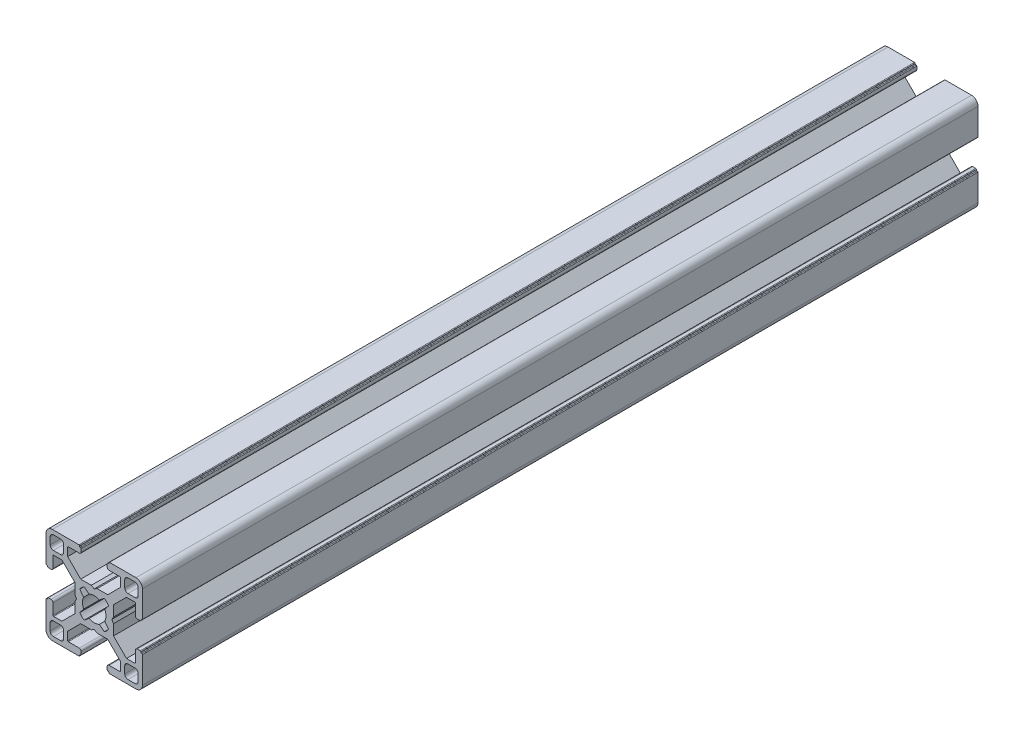
SolidWorks part; units mm, degrees
ref_plane "Front" through (0, 0, 0) normal (0, 0, 1) x (1, 0, 0)
ref_plane "Top" through (0, 0, 0) normal (0, 1, 0) x (1, 0, 0)
ref_plane "Right" through (0, 0, 0) normal (1, 0, 0) x (0, 0, -1)
sketch "Sketch1" plane through (0, 0, 0) normal (0, 0, 1) x (1, 0, 0)
  line L0 (13.7, 12.7) -> (13.7, 10.5)
  line L1 (10.5, 9.5) -> (12.7, 9.5)
  line L2 (9.5, 12.7) -> (9.5, 10.5)
  line L3 (10.5, 13.7) -> (12.7, 13.7)
  line L4 (3.1359, 4.5184) -> (1.6001, 3.2806)
  line L5 (3.2806, 1.6001) -> (4.5053, 3.1547)
  line L6 (6.0045, 0.9) -> (5.4849, 0)
  line L7 (6.0045, 4.2045) -> (6.0045, 0.9)
  line L8 (0, -5.4849) -> (0.9, -6)
  line L9 (0.9, -6) -> (4.2045, -6)
  line L10 (4.2045, -6) -> (8.25, -10.05)
  line L11 (8.25, -10.05) -> (8.25, -12.6)
  line L12 (4.65, -12.8) -> (8.05, -12.8)
  line L13 (4.05, -14.3) -> (4.05, -13.4)
  line L14 (4.25, -14.5) -> (4.35, -14.5)
  line L15 (4.55, -14.8) -> (4.55, -14.7)
  line L16 (4.75, -15) -> (13, -15)
  line L17 (15, -13) -> (15, -4.75)
  line L18 (14.7, -4.55) -> (14.8, -4.55)
  line L19 (14.5, -4.35) -> (14.5, -4.25)
  line L20 (13.4, -4.05) -> (14.3, -4.05)
  line L21 (12.8, -8.05) -> (12.8, -4.65)
  line L22 (12.6, -8.25) -> (10.05, -8.25)
  line L23 (10.05, -8.25) -> (6.0045, -4.2045)
  line L24 (6.0045, -4.2045) -> (6.0045, -0.9)
  line L25 (6.0045, -0.9) -> (5.4849, 0)
  line L26 (10.05, 8.25) -> (6.0045, 4.2045)
  line L27 (12.6, 8.25) -> (10.05, 8.25)
  line L28 (12.8, 8.05) -> (12.8, 4.65)
  line L29 (13.4, 4.05) -> (14.3, 4.05)
  line L30 (14.5, 4.35) -> (14.5, 4.25)
  line L31 (14.7, 4.55) -> (14.8, 4.55)
  line L32 (15, 13) -> (15, 4.75)
  line L33 (4.75, 15) -> (13, 15)
  line L34 (4.55, 14.8) -> (4.55, 14.7)
  line L35 (4.25, 14.5) -> (4.35, 14.5)
  line L36 (4.05, 14.3) -> (4.05, 13.4)
  line L37 (4.65, 12.8) -> (8.05, 12.8)
  line L38 (8.25, 10.05) -> (8.25, 12.6)
  line L39 (4.2045, 6) -> (8.25, 10.05)
  line L40 (0.9, 6) -> (4.2045, 6)
  line L41 (0, 5.4849) -> (0.9, 6)
  line L42 (-13.7, -12.7) -> (-13.7, -10.5)
  line L43 (-10.5, -9.5) -> (-12.7, -9.5)
  line L44 (-9.5, -12.7) -> (-9.5, -10.5)
  line L45 (-10.5, -13.7) -> (-12.7, -13.7)
  line L46 (-3.1359, -4.5184) -> (-1.6001, -3.2806)
  line L47 (-3.2806, -1.6001) -> (-4.5053, -3.1547)
  line L48 (0, 5.4849) -> (-0.9, 6)
  line L49 (-0.9, 6) -> (-4.2045, 6)
  line L50 (-4.2045, 6) -> (-8.25, 10.05)
  line L51 (-8.25, 10.05) -> (-8.25, 12.6)
  line L52 (-4.65, 12.8) -> (-8.05, 12.8)
  line L53 (-4.05, 14.3) -> (-4.05, 13.4)
  line L54 (-4.25, 14.5) -> (-4.35, 14.5)
  line L55 (-4.55, 14.8) -> (-4.55, 14.7)
  line L56 (-4.75, 15) -> (-13, 15)
  line L57 (-15, 13) -> (-15, 4.75)
  line L58 (-14.7, 4.55) -> (-14.8, 4.55)
  line L59 (-14.5, 4.35) -> (-14.5, 4.25)
  line L60 (-13.4, 4.05) -> (-14.3, 4.05)
  line L61 (-12.8, 8.05) -> (-12.8, 4.65)
  line L62 (-12.6, 8.25) -> (-10.05, 8.25)
  line L63 (-10.05, 8.25) -> (-6.0045, 4.2045)
  line L64 (-6.0045, -0.9) -> (-5.4849, 0)
  line L65 (-6.0045, -4.2045) -> (-6.0045, -0.9)
  line L66 (-10.05, -8.25) -> (-6.0045, -4.2045)
  line L67 (-12.6, -8.25) -> (-10.05, -8.25)
  line L68 (-12.8, -8.05) -> (-12.8, -4.65)
  line L69 (-13.4, -4.05) -> (-14.3, -4.05)
  line L70 (-14.5, -4.35) -> (-14.5, -4.25)
  line L71 (-14.7, -4.55) -> (-14.8, -4.55)
  line L72 (-15, -13) -> (-15, -4.75)
  line L73 (-4.75, -15) -> (-13, -15)
  line L74 (-4.55, -14.8) -> (-4.55, -14.7)
  line L75 (-4.25, -14.5) -> (-4.35, -14.5)
  line L76 (-4.05, -14.3) -> (-4.05, -13.4)
  line L77 (3.2806, -1.6001) -> (4.5053, -3.1547)
  line L78 (3.1359, -4.5184) -> (1.6001, -3.2806)
  line L79 (-4.65, -12.8) -> (-8.05, -12.8)
  line L80 (-8.25, -10.05) -> (-8.25, -12.6)
  line L81 (-4.2045, -6) -> (-8.25, -10.05)
  line L82 (-0.9, -6) -> (-4.2045, -6)
  line L83 (0, -5.4849) -> (-0.9, -6)
  line L84 (10.5, -13.7) -> (12.7, -13.7)
  line L85 (9.5, -12.7) -> (9.5, -10.5)
  line L86 (10.5, -9.5) -> (12.7, -9.5)
  line L87 (13.7, -12.7) -> (13.7, -10.5)
  line L88 (-6.0045, 4.2045) -> (-6.0045, 0.9)
  line L89 (-6.0045, 0.9) -> (-5.4849, 0)
  line L90 (-3.2806, 1.6001) -> (-4.5053, 3.1547)
  line L91 (-3.1359, 4.5184) -> (-1.6001, 3.2806)
  line L92 (-10.5, 13.7) -> (-12.7, 13.7)
  line L93 (-9.5, 12.7) -> (-9.5, 10.5)
  line L94 (-10.5, 9.5) -> (-12.7, 9.5)
  line L95 (-13.7, 12.7) -> (-13.7, 10.5)
  line L96 (-23.4857, 0) -> (20.9308, 0) construction
  line L97 (0, 17.9563) -> (0, -17.361) construction
  arc A0 (13.7, 12.7) -> (12.7, 13.7) centre (12.7, 12.7) ccw
  arc A1 (12.7, 9.5) -> (13.7, 10.5) centre (12.7, 10.5) ccw
  arc A2 (9.5, 10.5) -> (10.5, 9.5) centre (10.5, 10.5) ccw
  arc A3 (10.5, 13.7) -> (9.5, 12.7) centre (10.5, 12.7) ccw
  arc A4 (1.6001, 3.2806) -> (-1.6001, 3.2806) centre (0, 0) ccw
  arc A5 (8.25, -12.6) -> (8.05, -12.8) centre (8.05, -12.6) cw
  arc A6 (4.65, -12.8) -> (4.05, -13.4) centre (4.65, -13.4) ccw
  arc A7 (4.05, -14.3) -> (4.25, -14.5) centre (4.25, -14.3) ccw
  arc A8 (4.35, -14.5) -> (4.55, -14.7) centre (4.35, -14.7) cw
  arc A9 (4.55, -14.8) -> (4.75, -15) centre (4.75, -14.8) ccw
  arc A10 (13, -15) -> (15, -13) centre (13, -13) ccw
  arc A11 (15, -4.75) -> (14.8, -4.55) centre (14.8, -4.75) ccw
  arc A12 (14.7, -4.55) -> (14.5, -4.35) centre (14.7, -4.35) cw
  arc A13 (14.5, -4.25) -> (14.3, -4.05) centre (14.3, -4.25) ccw
  arc A14 (13.4, -4.05) -> (12.8, -4.65) centre (13.4, -4.65) ccw
  arc A15 (12.8, -8.05) -> (12.6, -8.25) centre (12.6, -8.05) cw
  arc A16 (4.5053, 3.1547) -> (3.1359, 4.5184) centre (0, 0) ccw
  arc A17 (12.8, 8.05) -> (12.6, 8.25) centre (12.6, 8.05) ccw
  arc A18 (13.4, 4.05) -> (12.8, 4.65) centre (13.4, 4.65) cw
  arc A19 (14.5, 4.25) -> (14.3, 4.05) centre (14.3, 4.25) cw
  arc A20 (14.7, 4.55) -> (14.5, 4.35) centre (14.7, 4.35) ccw
  arc A21 (15, 4.75) -> (14.8, 4.55) centre (14.8, 4.75) cw
  arc A22 (13, 15) -> (15, 13) centre (13, 13) cw
  arc A23 (4.55, 14.8) -> (4.75, 15) centre (4.75, 14.8) cw
  arc A24 (4.35, 14.5) -> (4.55, 14.7) centre (4.35, 14.7) ccw
  arc A25 (4.05, 14.3) -> (4.25, 14.5) centre (4.25, 14.3) cw
  arc A26 (4.65, 12.8) -> (4.05, 13.4) centre (4.65, 13.4) cw
  arc A27 (8.25, 12.6) -> (8.05, 12.8) centre (8.05, 12.6) ccw
  arc A28 (-13.7, -12.7) -> (-12.7, -13.7) centre (-12.7, -12.7) ccw
  arc A29 (-12.7, -9.5) -> (-13.7, -10.5) centre (-12.7, -10.5) ccw
  arc A30 (-9.5, -10.5) -> (-10.5, -9.5) centre (-10.5, -10.5) ccw
  arc A31 (-10.5, -13.7) -> (-9.5, -12.7) centre (-10.5, -12.7) ccw
  arc A32 (-4.5053, -3.1547) -> (-3.1359, -4.5184) centre (0, 0) ccw
  arc A33 (-3.2806, 1.6001) -> (-3.2806, -1.6001) centre (0, 0) ccw
  arc A34 (-8.25, 12.6) -> (-8.05, 12.8) centre (-8.05, 12.6) cw
  arc A35 (-4.65, 12.8) -> (-4.05, 13.4) centre (-4.65, 13.4) ccw
  arc A36 (-4.05, 14.3) -> (-4.25, 14.5) centre (-4.25, 14.3) ccw
  arc A37 (-4.35, 14.5) -> (-4.55, 14.7) centre (-4.35, 14.7) cw
  arc A38 (-4.55, 14.8) -> (-4.75, 15) centre (-4.75, 14.8) ccw
  arc A39 (-13, 15) -> (-15, 13) centre (-13, 13) ccw
  arc A40 (-15, 4.75) -> (-14.8, 4.55) centre (-14.8, 4.75) ccw
  arc A41 (-14.7, 4.55) -> (-14.5, 4.35) centre (-14.7, 4.35) cw
  arc A42 (-14.5, 4.25) -> (-14.3, 4.05) centre (-14.3, 4.25) ccw
  arc A43 (-13.4, 4.05) -> (-12.8, 4.65) centre (-13.4, 4.65) ccw
  arc A44 (-12.8, 8.05) -> (-12.6, 8.25) centre (-12.6, 8.05) cw
  arc A45 (-4.5053, 3.1547) -> (-3.1359, 4.5184) centre (0, 0) cw
  arc A46 (-12.8, -8.05) -> (-12.6, -8.25) centre (-12.6, -8.05) ccw
  arc A47 (-13.4, -4.05) -> (-12.8, -4.65) centre (-13.4, -4.65) cw
  arc A48 (-14.5, -4.25) -> (-14.3, -4.05) centre (-14.3, -4.25) cw
  arc A49 (3.2806, 1.6001) -> (3.2806, -1.6001) centre (0, 0) cw
  arc A50 (4.5053, -3.1547) -> (3.1359, -4.5184) centre (0, 0) cw
  arc A51 (1.6001, -3.2806) -> (-1.6001, -3.2806) centre (0, 0) cw
  arc A52 (-14.7, -4.55) -> (-14.5, -4.35) centre (-14.7, -4.35) ccw
  arc A53 (-15, -4.75) -> (-14.8, -4.55) centre (-14.8, -4.75) cw
  arc A54 (-13, -15) -> (-15, -13) centre (-13, -13) cw
  arc A55 (-4.55, -14.8) -> (-4.75, -15) centre (-4.75, -14.8) cw
  arc A56 (10.5, -13.7) -> (9.5, -12.7) centre (10.5, -12.7) cw
  arc A57 (9.5, -10.5) -> (10.5, -9.5) centre (10.5, -10.5) cw
  arc A58 (12.7, -9.5) -> (13.7, -10.5) centre (12.7, -10.5) cw
  arc A59 (13.7, -12.7) -> (12.7, -13.7) centre (12.7, -12.7) cw
  arc A60 (-4.35, -14.5) -> (-4.55, -14.7) centre (-4.35, -14.7) ccw
  arc A61 (-4.05, -14.3) -> (-4.25, -14.5) centre (-4.25, -14.3) cw
  arc A62 (-4.65, -12.8) -> (-4.05, -13.4) centre (-4.65, -13.4) cw
  arc A63 (-8.25, -12.6) -> (-8.05, -12.8) centre (-8.05, -12.6) ccw
  arc A64 (-10.5, 13.7) -> (-9.5, 12.7) centre (-10.5, 12.7) cw
  arc A65 (-9.5, 10.5) -> (-10.5, 9.5) centre (-10.5, 10.5) cw
  arc A66 (-12.7, 9.5) -> (-13.7, 10.5) centre (-12.7, 10.5) cw
  arc A67 (-13.7, 12.7) -> (-12.7, 13.7) centre (-12.7, 12.7) cw
  point P81 (15, 15)
  point P82 (0, 15)
  point P203 (0, -15)
  point P204 (15, -15)
  point P206 (0, 0)
  point P207 (15, 0)
  point P219 (-15, 0)
  point P220 (-15, -15)
  point P221 (-15, 15)
  dimension "D6" = 7.3
  dimension "D7" = 11
  dimension "D1" = 30
  dimension "D2" = 15
  dimension "D3" = 30
  dimension "D4" = 8.1
  dimension "D5" = 9
  dimension "D8" = 8.1
extrude "Base-Extrude" add sketch "Sketch1" against normal blind 260
